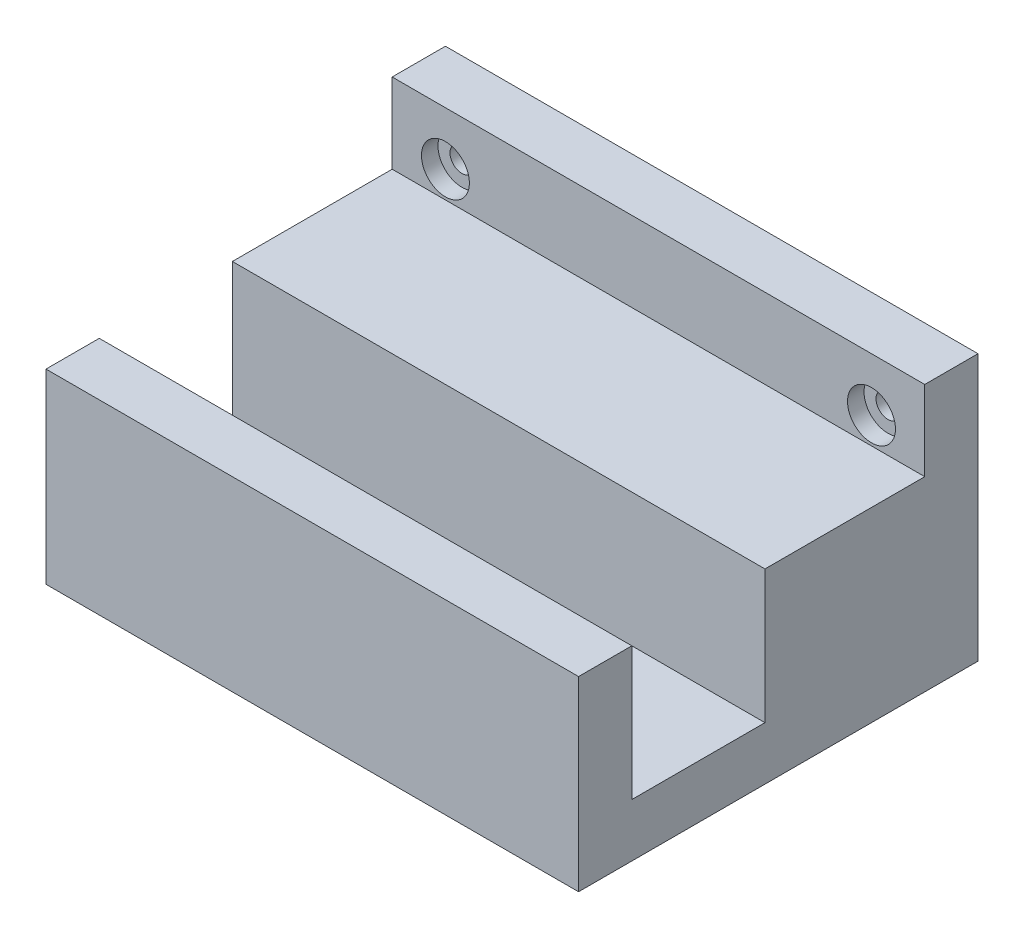
SolidWorks part; units mm, degrees
ref_plane "Alzado" through (0, 0, 0) normal (0, 0, 1) x (1, 0, 0)
ref_plane "Planta" through (0, 0, 0) normal (0, 1, 0) x (1, 0, 0)
ref_plane "Vista lateral" through (0, 0, 0) normal (1, 0, 0) x (0, 0, -1)
sketch "Croquis1" plane through (0, 0, 0) normal (0, 0, 1) x (1, 0, 0)
  line L1 (-50, -25) -> (50, -25)
  line L2 (-50, -25) -> (-50, 25)
  line L3 (-50, 25) -> (50, 25)
  line L4 (50, -25) -> (50, 25)
  line L5 (-50, -25) -> (50, 25) construction
  line L6 (-50, 25) -> (50, -25) construction
  point P0 (0, 0)
  dimension "D1" = 100
  dimension "D2" = 50
extrude "Saliente-Extruir1" add sketch "Croquis1" along normal blind 10
sketch "Croquis2" plane through (0, 0, 0) normal (0, 0, 1) x (1, 0, 0)
  line L0 (50, -25) -> (50, 25) construction
  line L1 (-50, -25) -> (50, -25)
  line L2 (-50, -25) -> (-50, -15)
  line L3 (-50, -15) -> (50, -15)
  line L4 (50, -25) -> (50, -15)
  dimension "D1" = 10
extrude "Saliente-Extruir2" add sketch "Croquis2" along normal blind 75
sketch "Croquis3" plane through (0, 0, 75) normal (0, 0, 1) x (1, 0, 0)
  line L1 (-50, 10) -> (50, 10)
  line L2 (-50, 10) -> (-50, -25)
  line L3 (-50, -25) -> (50, -25)
  line L4 (50, 10) -> (50, -25)
  dimension "D1" = 35
extrude "Saliente-Extruir3" add sketch "Croquis3" against normal blind 10
sketch "Croquis9" plane through (0, 0, 10) normal (0, 0, 1) x (1, 0, 0)
  line L0 (-50, 25) -> (-50, -15) construction
  line L1 (50, -15) -> (50, 25) construction
  line L2 (50, 25) -> (-50, 25) construction
  point P0 (-40, 15)
  point P1 (40, 15)
  dimension "D1" = 10
  dimension "D2" = 10
  dimension "D3" = 10
hole_wizard "Refrentado para tornillo con cabeza troncocónica de M43" positions "Croquis3D3" profile "Croquis10" counterbore size "M4" standard "ISO" end condition through all
sketch3d "Croquis3D3"
  point P0 (-40, 15, 10)
  point P4 (40, 15, 10)
sketch "Croquis10" plane through (-40, 15, 10) normal (1, 0, 0) x (0, -1, 0)
  line L0 (0, 0) -> (0, 10)
  line L1 (0, 10) -> (2.25, 10)
  line L3 (2.25, 10) -> (2.25, 3.1)
  line L4 (2.25, 3.1) -> (4.5, 3.1)
  line L5 (4.5, 3.1) -> (4.5, 0)
  line L7 (4.5, 0) -> (0, 0)
  line L11 (0, -6.35) -> (0, 107.95) construction
  dimension "Diámetro de taladro hasta el siguiente" = 4.5
  dimension "Profundidad de taladro hasta el siguiente" = 10
  dimension "Diámetro de refrentado" = 9
  dimension "Profundidad de refrentado" = 3.1
sketch "Croquis11" plane through (0, 0, 10) normal (0, 0, 1) x (1, 0, 0)
  line L1 (-50, 10) -> (50, 10)
  line L2 (-50, 10) -> (-50, -25)
  line L3 (-50, -25) -> (50, -25)
  line L4 (50, 10) -> (50, -25)
extrude "Saliente-Extruir4" add sketch "Croquis11" along normal blind 30
